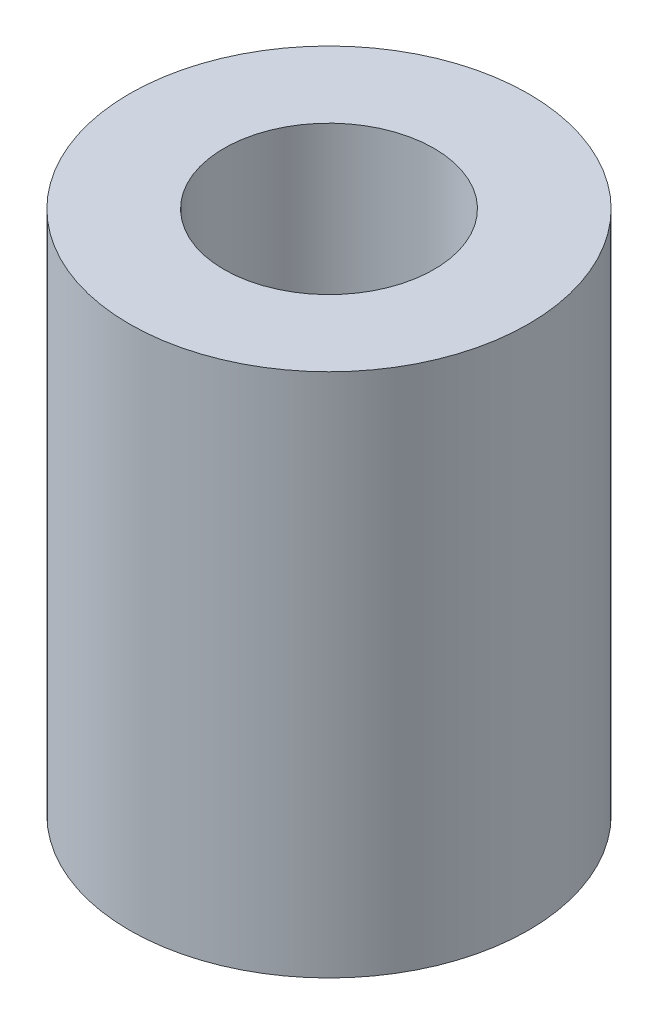
SolidWorks part; units mm, degrees
ref_plane "Front Plane" through (0, 0, 0) normal (0, 0, 1) x (1, 0, 0)
ref_plane "Top Plane" through (0, 0, 0) normal (0, 1, 0) x (1, 0, 0)
ref_plane "Right Plane" through (0, 0, 0) normal (1, 0, 0) x (0, 0, -1)
sketch "Sketch1" plane through (0, 0, 0) normal (0, 1, 0) x (1, 0, 0)
  circle A0 centre (0, 0) radius 9.5
  dimension "D1" = 19
extrude "Boss-Extrude1" add sketch "Sketch1" along normal blind 25
sketch "Sketch2" plane through (0, 25, 0) normal (0, 1, 0) x (1, 0, 0)
  circle A0 centre (0, 0) radius 5
  dimension "D1" = 10
extrude "Cut-Extrude1" cut sketch "Sketch2" against normal blind 17.5
sketch "Sketch3" plane through (0, 7.5, 0) normal (0, 1, 0) x (1, 0, 0)
  circle A0 centre (0, 0) radius 4
  dimension "D1" = 8
extrude "Cut-Extrude2" cut sketch "Sketch3" against normal through all
